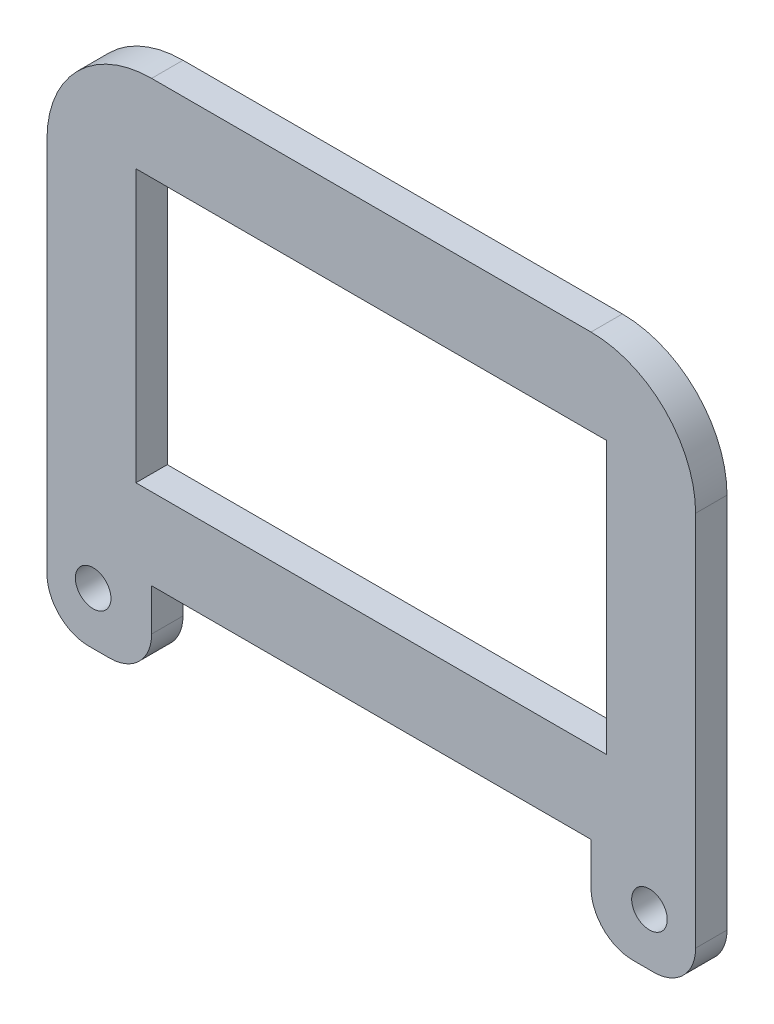
SolidWorks part; units mm, degrees
material "PVC rigido"
ref_plane "Piano frontale" through (0, 0, 0) normal (0, 0, 1) x (1, 0, 0)
ref_plane "Piano superiore" through (0, 0, 0) normal (0, 1, 0) x (1, 0, 0)
ref_plane "Piano destro" through (0, 0, 0) normal (1, 0, 0) x (0, 0, -1)
sketch "Schizzo2" plane through (0, 0, 0) normal (0, 0, 1) x (1, 0, 0)
  line L1 (31, -25) -> (-31, -25)
  line L2 (31, -25) -> (31, 25)
  line L3 (31, 25) -> (-31, 25)
  line L4 (-31, -25) -> (-31, 25)
  line L5 (31, -25) -> (-31, 25) construction
  line L6 (31, 25) -> (-31, -25) construction
  point P0 (0, 0)
  dimension "D1" = 62
  dimension "D2" = 50
extrude "Estrusione-Estrusione1" add sketch "Schizzo2" along normal blind 3
hole_wizard "Foro per Vite M3-1" positions "Schizzo4" profile "Schizzo3" hole size "M3" standard "Ansi Metric" end condition through all
sketch "Schizzo4" plane through (0, 0, 3) normal (0, 0, 1) x (1, 0, 0)
  line L0 (-26.5864, -20) -> (26.5864, -20) construction
  line L1 (26.5864, -20) -> (31, -20) construction
  line L2 (31, -25) -> (31, 25) construction
  line L4 (-26.5864, -20) -> (-31, -20) construction
  line L5 (-31, 25) -> (-31, -25) construction
  circle A0 centre (26.5864, -20) radius 1.25 construction
  circle A1 centre (-26.5864, -20) radius 1.25 construction
  point P0 (-26.5864, -20)
  point P2 (26.5864, -20)
sketch "Schizzo3" plane through (-26.5864, -20, 3) normal (1, 0, 0) x (0, -1, 0)
  line L0 (0, 0) -> (0, 3)
  line L1 (0, 3) -> (1.7, 3)
  line L2 (1.7, 3) -> (1.7, 0)
  line L5 (1.7, 0) -> (0, 0)
  line L11 (0, -6.35) -> (0, 107.95) construction
  dimension "Thru Hole Dia." = 3.4
  dimension "Thru Hole Depth" = 3
sketch "Schizzo5" plane through (0, 0, 3) normal (0, 0, 1) x (1, 0, 0)
  line L0 (-31, -25) -> (31, -25) construction
  line L1 (-21, -25) -> (21, -25)
  line L2 (-21, -25) -> (-21, -17)
  line L3 (-21, -17) -> (21, -17)
  line L4 (21, -25) -> (21, -17)
  line L5 (0, 0) -> (0, -17) construction
  dimension "D1" = 42
  dimension "D2" = 8
extrude "Taglio-Estrusione1" cut sketch "Schizzo5" against normal blind 3
sketch "Schizzo6" plane through (0, 0, 3) normal (0, 0, 1) x (1, 0, 0)
  line L0 (-22.5, 3.7721) -> (-31, 3.7721) construction
  line L1 (22.5, -9.2279) -> (-22.5, -9.2279)
  line L2 (22.5, -9.2279) -> (22.5, 16.7721)
  line L3 (22.5, 16.7721) -> (-22.5, 16.7721)
  line L4 (-22.5, -9.2279) -> (-22.5, 16.7721)
  line L5 (22.5, -9.2279) -> (-22.5, 16.7721) construction
  line L6 (22.5, 16.7721) -> (-22.5, -9.2279) construction
  line L7 (-31, 25) -> (-31, -25) construction
  line L8 (22.5, 3.7721) -> (31, 3.7721) construction
  line L9 (31, -25) -> (31, 25) construction
  point P0 (0, 3.7721)
  dimension "D1" = 45
  dimension "D2" = 26
extrude "Taglio-Estrusione2" cut sketch "Schizzo6" against normal blind 3
fillet "Raccordo1" radius 10 2 edges at (-31, 25, 1.5) (31, 25, 1.5)
fillet "Raccordo2" radius 4 4 edges at (21, -25, 1.5) (31, -25, 1.5) (-21, -25, 1.5) (-31, -25, 1.5)
